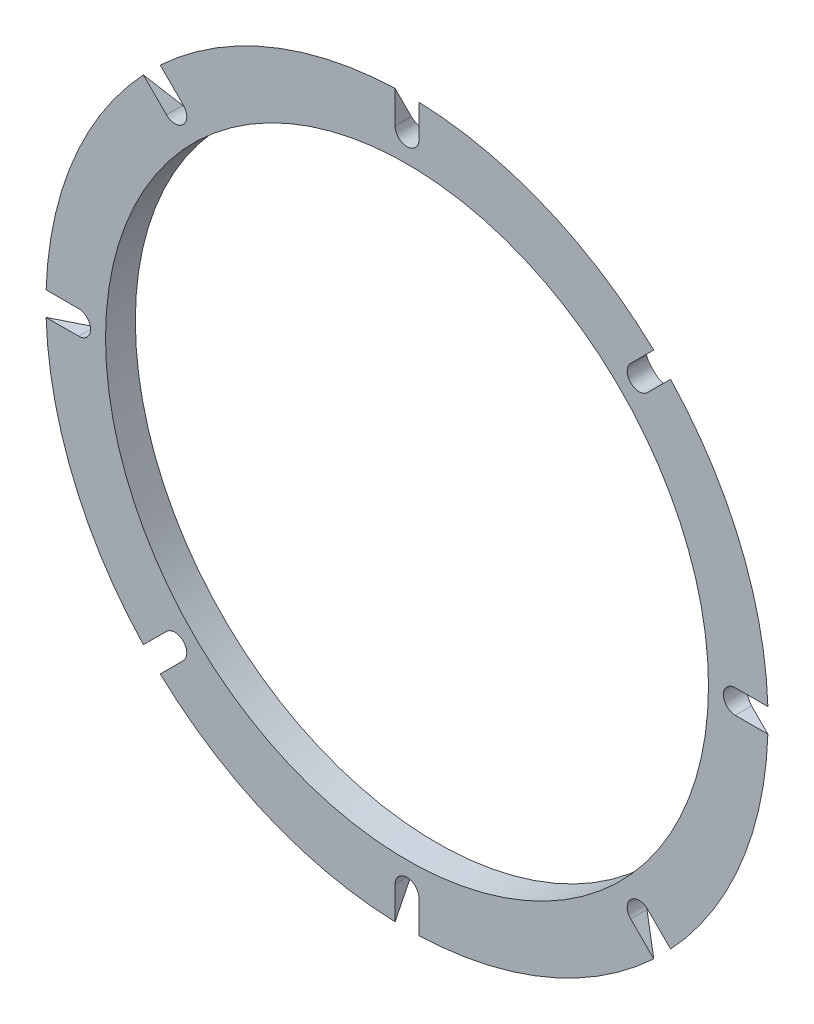
SolidWorks part; units mm, degrees
ref_plane "Front Plane" through (0, 0, 0) normal (0, 0, 1) x (1, 0, 0)
ref_plane "Top Plane" through (0, 0, 0) normal (0, 1, 0) x (1, 0, 0)
ref_plane "Right Plane" through (0, 0, 0) normal (1, 0, 0) x (0, 0, -1)
sketch "Sketch2" plane through (0, 0, 0) normal (1, 0, 0) x (0, 0, -1)
  line L0 (-25.6168, 0) -> (38.079, 0) construction
  line L1 (55, 0) -> (-55, 0) construction
  line L2 (0, 121.15) -> (0, 101.15)
  line L3 (0, 55) -> (0, -55) construction
  line L4 (0, 101.15) -> (10, 101.15)
  line L5 (10, 101.15) -> (0, 121.15)
  dimension "D1" = 101.15
  dimension "D2" = 20
  dimension "D3" = 10
revolve "Revolve1" add sketch "Sketch2" angle 360 about L0
sketch "Sketch3" plane through (0, 0, 0) normal (0, 0, 1) x (1, 0, 0)
  line L0 (0, -35.0327) -> (0, 35.0327) construction
  line L1 (35.0327, 0) -> (-35.0327, 0) construction
  line L2 (-4, 110.15) -> (-4, 131.3727)
  line L3 (-4, 131.3727) -> (4, 131.3727)
  line L4 (4, 131.3727) -> (4, 110.15)
  arc A0 (-4, 110.15) -> (4, 110.15) centre (0, 110.15) ccw
  dimension "D1" = 110.15
  dimension "D2" = 8
extrude "Cut-Extrude1" cut sketch "Sketch3" against normal blind 10
pattern_circular "CirPattern1" count 8 over 360 about axis through (0, 0, 0) along (0, 0, 1) of "Cut-Extrude1"
